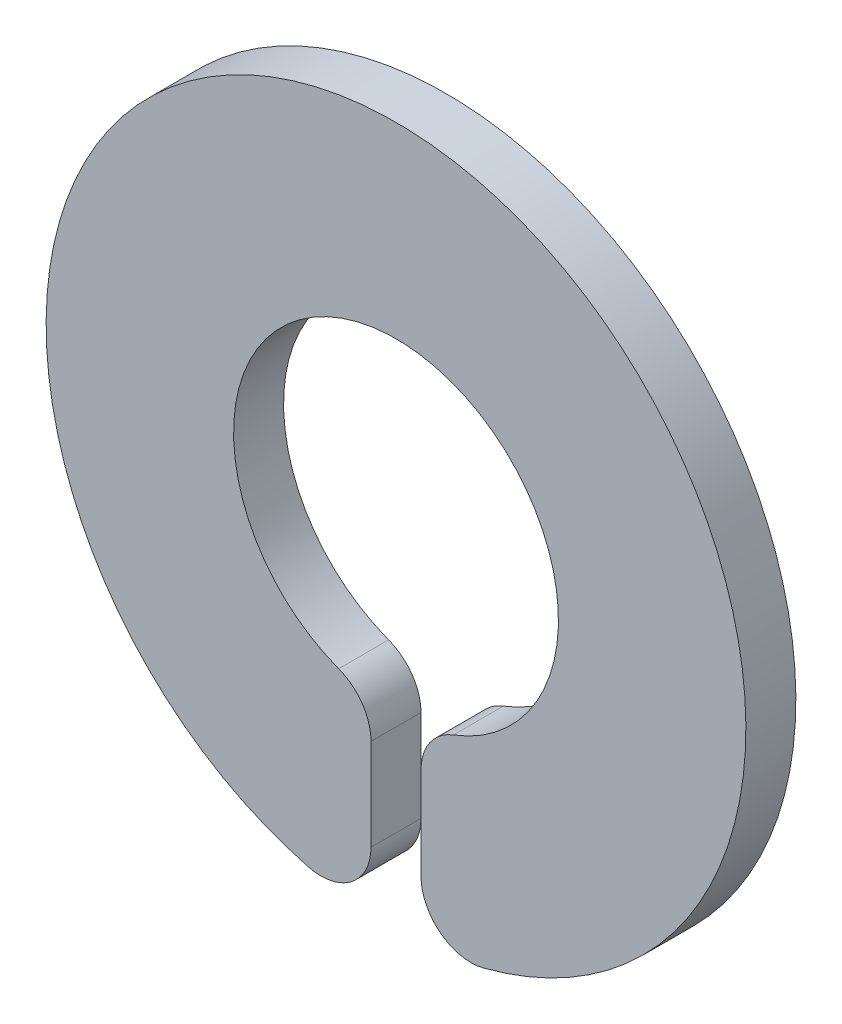
SolidWorks part; units mm, degrees
ref_plane "Přední rovina" through (0, 0, 0) normal (0, 0, 1) x (1, 0, 0)
ref_plane "Horní rovina" through (0, 0, 0) normal (0, 1, 0) x (1, 0, 0)
ref_plane "Pravá rovina" through (0, 0, 0) normal (1, 0, 0) x (0, 0, -1)
sketch "Skica1" plane through (0, 0, 0) normal (0, 0, 1) x (1, 0, 0)
  line L0 (-0.5, -3.2113) -> (-0.5, -6.9821)
  line L1 (0, 0) -> (0, -6.9821) construction
  line L2 (0.5, -3.2113) -> (0.5, -6.9821)
  arc A0 (0.5, -6.9821) -> (-0.5, -6.9821) centre (0, 0) ccw
  arc A1 (0.5, -3.2113) -> (-0.5, -3.2113) centre (0, 0) ccw
  dimension "D1" = 6.5
  dimension "D2" = 14
  dimension "D3" = 0.5
extrude "Přidat vysunutím1" add sketch "Skica1" along normal blind 1
fillet "Zaoblit1" radius 1 4 edges at (0.5, -6.9821, 0.5) (-0.5, -6.9821, 0.5) (0.5, -3.2113, 0.5) (-0.5, -3.2113, 0.5)
